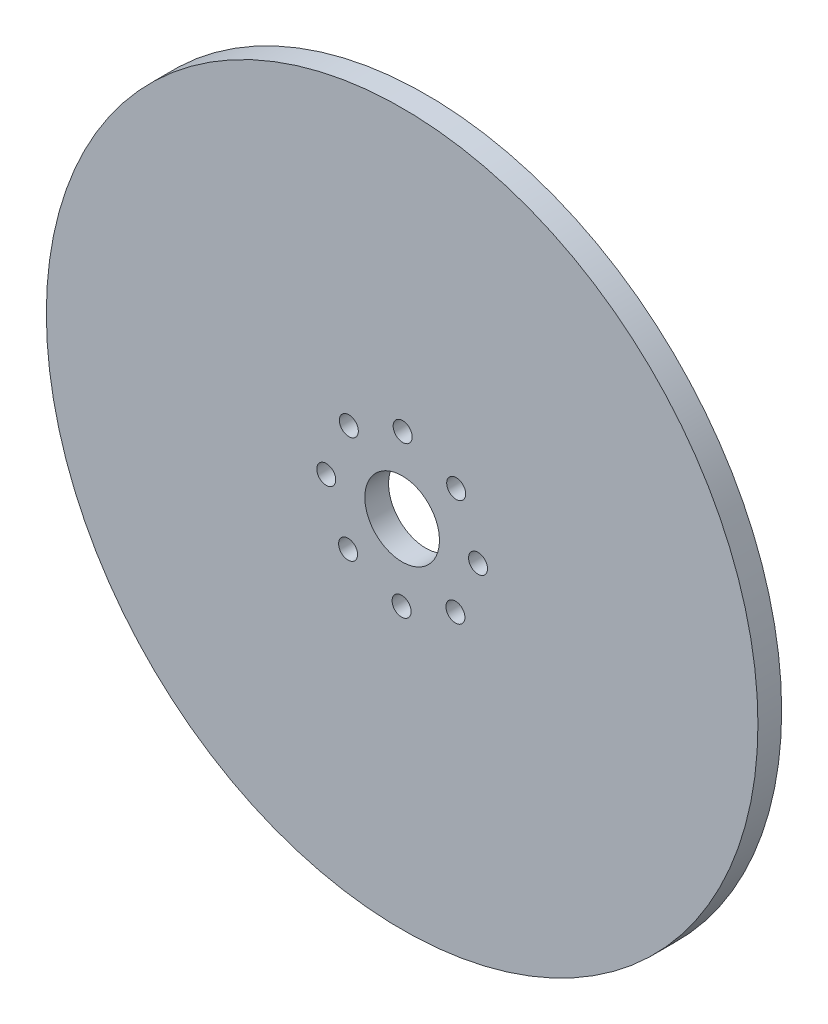
SolidWorks part; units mm, degrees
ref_plane "Front Plane" through (0, 0, 0) normal (0, 0, 1) x (1, 0, 0)
ref_plane "Top Plane" through (0, 0, 0) normal (0, 1, 0) x (1, 0, 0)
ref_plane "Right Plane" through (0, 0, 0) normal (1, 0, 0) x (0, 0, -1)
sketch "Sketch1" plane through (0, 0, 0) normal (0, 0, 1) x (1, 0, 0)
  circle A5 centre (0, 0) radius 37.5
  dimension "D1" = 75
extrude "Boss-Extrude1" add sketch "Sketch1" along normal blind 2.5
sketch "Sketch2" plane through (0, 0, 0) normal (0, 0, -1) x (-1, 0, 0)
  circle A0 centre (0, 0) radius 3.9332
  circle A1 centre (0.0565, -7.9998) radius 1
  circle A2 centre (-5.6168, -5.6967) radius 1
  circle A3 centre (-7.9998, -0.0565) radius 1
  circle A4 centre (-5.6967, 5.6168) radius 1
  circle A5 centre (-0.0565, 7.9998) radius 1.0011
  circle A6 centre (5.6168, 5.6967) radius 1
  circle A7 centre (7.9998, 0.0565) radius 1
  circle A8 centre (5.6967, -5.6168) radius 1
extrude "Cut-Extrude1" cut sketch "Sketch2" against normal through all
